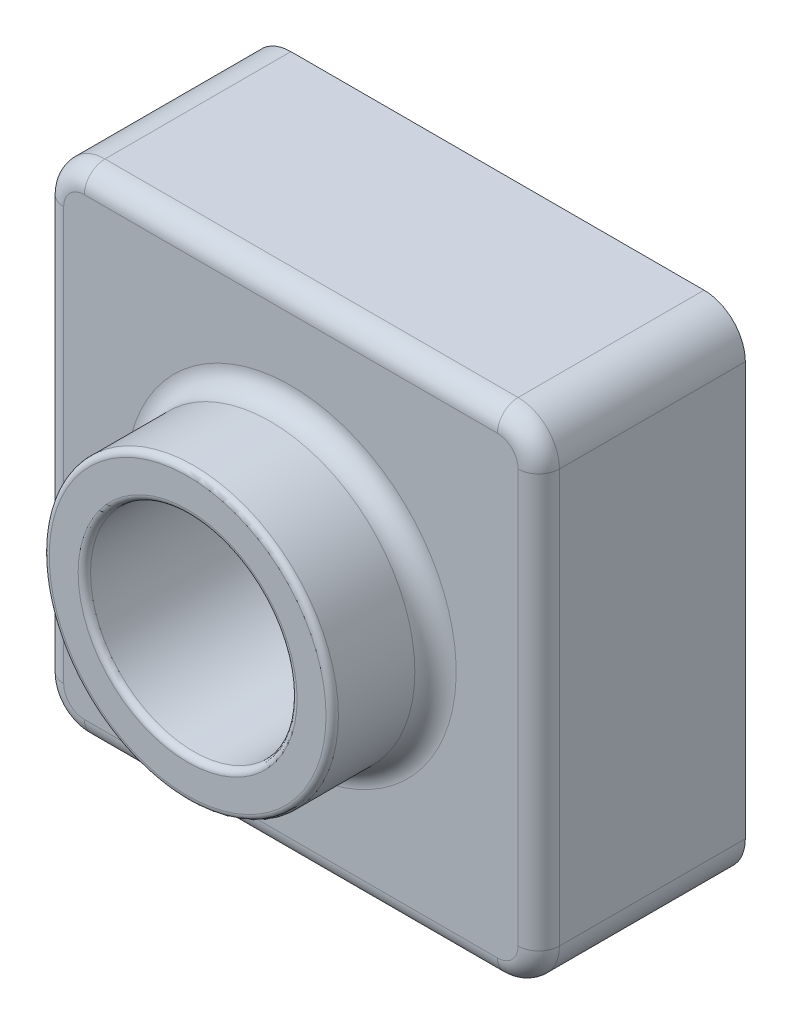
SolidWorks part; units mm, degrees
material "Nickel"
ref_plane "Front Plane" through (0, 0, 0) normal (0, 0, 1) x (1, 0, 0)
ref_plane "Top Plane" through (0, 0, 0) normal (0, 1, 0) x (1, 0, 0)
ref_plane "Right Plane" through (0, 0, 0) normal (1, 0, 0) x (0, 0, -1)
sketch "Sketch1" plane through (0, 0, 0) normal (0, 0, 1) x (1, 0, 0)
  line L1 (0, 0) -> (120, 0)
  line L2 (0, 0) -> (0, 120)
  line L3 (0, 120) -> (120, 120)
  line L4 (120, 0) -> (120, 120)
  dimension "D1" = 120
  dimension "D2" = 120
extrude "Boss-Extrude2" add sketch "Sketch1" along normal blind 50 contours L3 L4 L1 L2
sketch "Sketch2" plane through (0, 0, 50) normal (0, 0, 1) x (1, 0, 0)
  line L0 (0, 120) -> (120, 120) construction
  line L1 (120, 0) -> (120, 120) construction
  circle A0 centre (60, 60) radius 35
  dimension "D1" = 70
  dimension "D2" = 60
  dimension "D3" = 60
extrude "Boss-Extrude3" add sketch "Sketch2" along normal blind 25
sketch "Sketch3" plane through (0, 0, 75) normal (0, 0, 1) x (1, 0, 0)
  circle A0 centre (60, 60) radius 25
  dimension "D1" = 50
extrude "Cut-Extrude1" cut sketch "Sketch3" against normal through all contours A0
fillet "Fillet1" radius 10 4 edges at (0, 0, 25) (0, 120, 25) (120, 0, 25) (120, 120, 25)
fillet "Fillet2" radius 1.5 2 edges at (95, 60, 75) (85, 60, 75)
fillet "Fillet3" radius 5 9 edges at (2.9289, 117.0711, 50) (60, 120, 50) (117.0711, 117.0711, 50) (120, 60, 50) (117.0711, 2.9289, 50) (60, 0, 50) (2.9289, 2.9289, 50) (0, 60, 50) (95, 60, 50)
shell "Shell1" thickness 2
